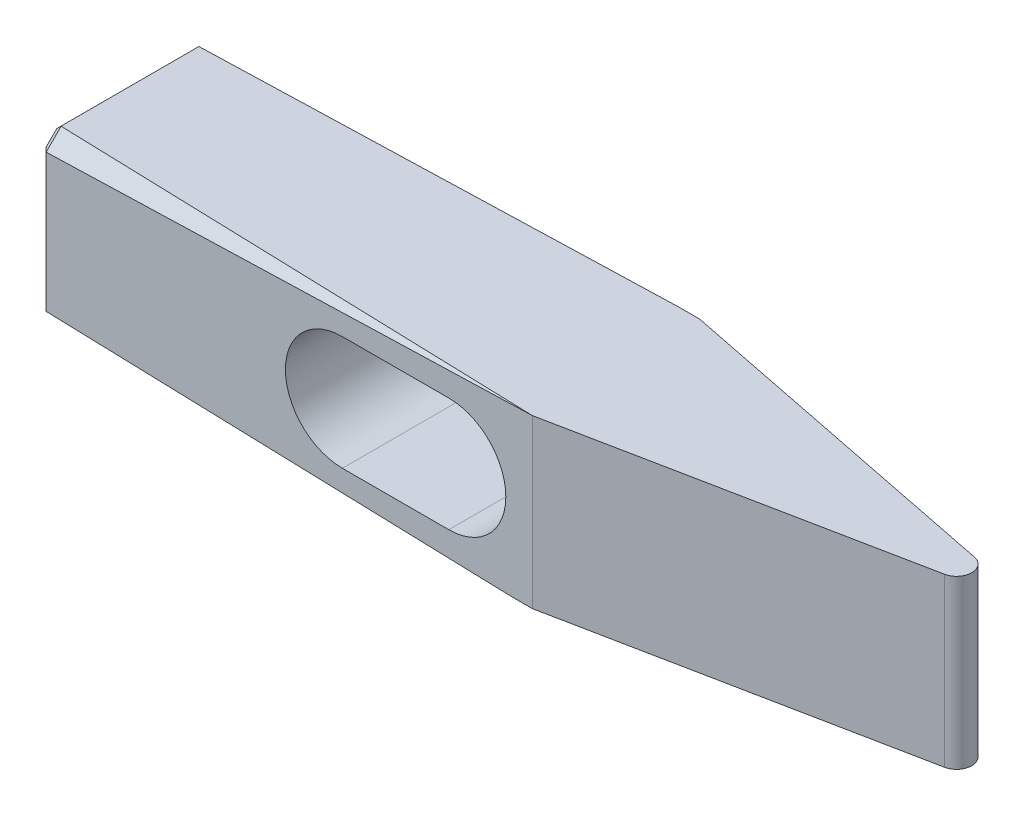
SolidWorks part; units mm, degrees
ref_plane "Ebene vorne" through (0, 0, 0) normal (0, 0, 1) x (1, 0, 0)
ref_plane "Ebene oben" through (0, 0, 0) normal (0, 1, 0) x (1, 0, 0)
ref_plane "Ebene rechts" through (0, 0, 0) normal (1, 0, 0) x (0, 0, -1)
sketch "Skizze1" plane through (0, 0, 0) normal (0, 0, 1) x (1, 0, 0)
  line L1 (0, 0) -> (120, 0)
  line L2 (0, 0) -> (0, 22)
  line L3 (0, 22) -> (120, 22)
  line L4 (120, 0) -> (120, 22)
  dimension "D1" = 120
  dimension "D2" = 22
extrude "Aufsatz-Linear austragen1" add sketch "Skizze1" along normal blind 22
sketch "Skizze2" plane through (0, 22, 0) normal (0, 1, 0) x (1, 0, 0)
  line L5 (120, -11) -> (65, -22)
  line L6 (120, -22) -> (120, 0) construction
  line L7 (0, -22) -> (120, -22) construction
  line L8 (65, -22) -> (120, -22)
  line L9 (120, -22) -> (120, -11)
  dimension "D1" = 55
extrude "Schnitt-Linear austragen1" cut sketch "Skizze2" against normal through all both and the other way through all
sketch "Skizze3" plane through (0, 0, 0) normal (0, -1, 0) x (1, 0, 0)
  line L0 (120, 11) -> (65, 0)
  line L2 (0, 0) -> (120, 0) construction
  line L3 (65, 0) -> (120, 0)
  line L5 (120, 0) -> (120, 11)
  dimension "D1" = 55
extrude "Schnitt-Linear austragen5" cut sketch "Skizze3" against normal through all
sketch "Skizze5" plane through (0, 0, 0) normal (0, 0, -1) x (-1, 0, 0)
  line L0 (0, 11) -> (-120, 11) construction
  line L1 (0, 22) -> (0, 0) construction
  line L2 (-120, 0) -> (-120, 22) construction
  line L3 (-54, 11) -> (-40, 11) construction
  line L4 (-54, 18.5) -> (-40, 18.5)
  line L5 (-54, 3.5) -> (-40, 3.5)
  arc A0 (-54, 18.5) -> (-54, 3.5) centre (-54, 11) ccw
  arc A1 (-40, 3.5) -> (-40, 18.5) centre (-40, 11) ccw
  point P8 (-47, 11)
  dimension "D1" = 15
  dimension "D2" = 14
  dimension "D3" = 40
extrude "Schnitt-Linear austragen6" cut sketch "Skizze5" against normal through all
fillet "Verrundung1" radius 2 1 edges at (120, 11, 11)
sketch3d "3D-Skizze1"
  line L6 (65, 22, 22) -> (0, 22, 20)
  line L7 (0, 22, 22) -> (0, 22, 0) construction
  line L8 (0, 22, 20) -> (0, 20, 22)
  line L9 (0, 22, 22) -> (0, 0, 22) construction
  line L10 (0, 20, 22) -> (65, 22, 22)
  dimension "D1" = 2
  dimension "D2" = 2
extrude "Schnitt-Linear austragen7" cut sketch "3D-Skizze1" along a picked direction on the side of the normal through all
pattern_circular "Kreismuster1" count 4 every 90 about axis through (0, 10.9571, 10.9571) along (1, 0, 0) of "Schnitt-Linear austragen7"
chamfer "Fase1" distance 1 angle 45 8 edges at (0, 0, 10.9571) (0, 10.9571, 0)
sketch "Skizze6" plane through (0, 0, 0) normal (-1, 0, 0) x (0, 0, 1)
  text T0 "GL"
extrude "Schnitt-Linear austragen8" cut sketch "Skizze6" against normal blind 10
